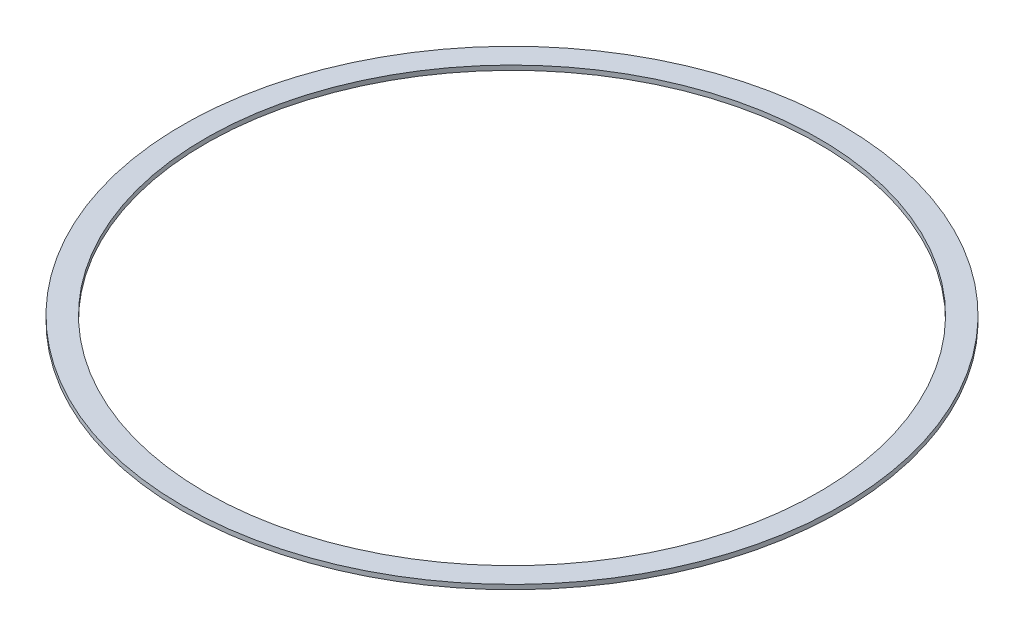
SolidWorks part; units mm, degrees
ref_plane "Front Plane" through (0, 0, 0) normal (0, 0, 1) x (1, 0, 0)
ref_plane "Top Plane" through (0, 0, 0) normal (0, 1, 0) x (1, 0, 0)
ref_plane "Right Plane" through (0, 0, 0) normal (1, 0, 0) x (0, 0, -1)
sketch "Sketch1" plane through (0, 0, 0) normal (0, 1, 0) x (1, 0, 0)
  line L0 (200, 0) -> (-200, 0) construction
  circle A0 centre (0, 0) radius 200
  circle A1 centre (0, 0) radius 215
  dimension "D1" = 400
  dimension "D2" = 430
extrude "Boss-Extrude1" add sketch "Sketch1" along normal mid plane 3
